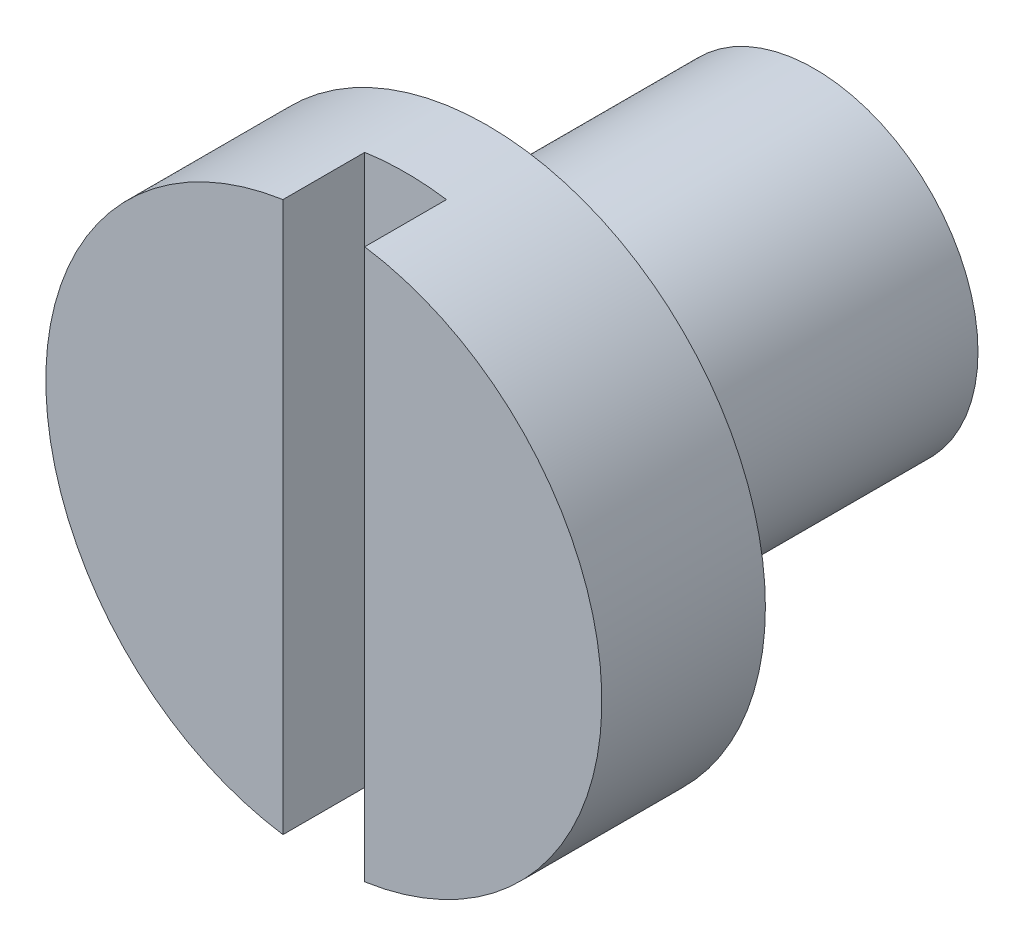
SolidWorks part; units mm, degrees
ref_plane "Front Plane" through (0, 0, 0) normal (0, 0, 1) x (1, 0, 0)
ref_plane "Top Plane" through (0, 0, 0) normal (0, 1, 0) x (1, 0, 0)
ref_plane "Right Plane" through (0, 0, 0) normal (1, 0, 0) x (0, 0, -1)
sketch "Sketch1" plane through (0, 0, 0) normal (0, 0, 1) x (1, 0, 0)
  circle A0 centre (0, 0) radius 10.795
  dimension "D1" = 21.59
extrude "Boss-Extrude1" add sketch "Sketch1" along normal mid plane 6.35
sketch "Sketch2" plane through (0, 0, -3.175) normal (0, 0, -1) x (-1, 0, 0)
  circle A0 centre (0, 0) radius 6.35
  dimension "D1" = 12.7
extrude "Boss-Extrude2" add sketch "Sketch2" along normal blind 12.7
sketch "Sketch3" plane through (0, 0, 3.175) normal (0, 0, 1) x (1, 0, 0)
  line L1 (1.5875, -12.7) -> (-1.5875, -12.7)
  line L2 (1.5875, -12.7) -> (1.5875, 12.7)
  line L3 (1.5875, 12.7) -> (-1.5875, 12.7)
  line L4 (-1.5875, -12.7) -> (-1.5875, 12.7)
  line L5 (1.5875, -12.7) -> (-1.5875, 12.7) construction
  line L6 (1.5875, 12.7) -> (-1.5875, -12.7) construction
  point P0 (0, 0)
  dimension "D1" = 3.175
  dimension "D2" = 25.4
extrude "Cut-Extrude1" cut sketch "Sketch3" against normal blind 3.175
